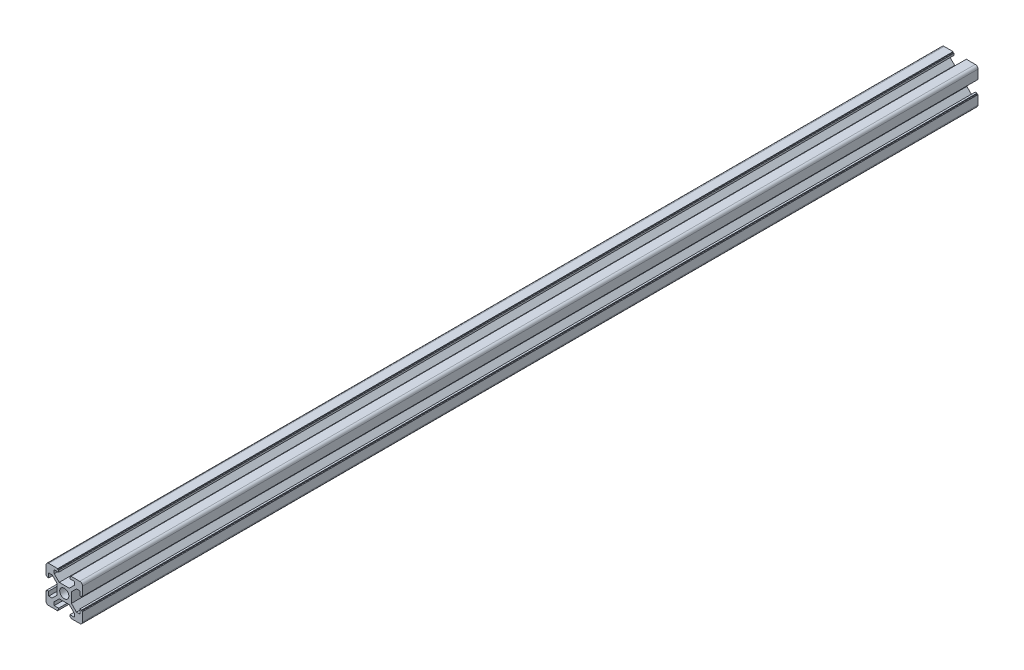
SolidWorks part; units mm, degrees
ref_plane "Plane1" through (0, 0, 0) normal (0, 0, 1) x (1, 0, 0)
ref_plane "Plane2" through (0, 0, 0) normal (0, 1, 0) x (1, 0, 0)
ref_plane "Plane3" through (0, 0, 0) normal (1, 0, 0) x (0, 0, -1)
sketch "Sketch1" plane through (0, 0, 0) normal (0, 0, 1) x (1, 0, 0)
  line L0 (-3.6, 10) -> (-3.6, 9.5)
  line L1 (-3.6, 9.5) -> (-3.1, 9.5)
  line L2 (-3.1, 9.5) -> (-3.1, 8.5)
  line L3 (-3.1, 8.5) -> (-5.5, 8.5)
  line L4 (-8.5, -10) -> (-3.6, -10)
  line L5 (-10, -8.5) -> (-10, -3.6)
  line L6 (8.5, 10) -> (3.6, 10)
  line L7 (10, 8.5) -> (10, 3.6)
  line L8 (0, 14.8756) -> (0, 0) construction
  line L9 (0, 0) -> (14.1675, 0) construction
  line L10 (-5.5, 8.5) -> (-5.5, 6.65)
  line L11 (-5.5, 6.65) -> (-2.75, 3.9)
  line L12 (-2.75, 3.9) -> (2.75, 3.9)
  line L13 (5.5, 6.65) -> (2.75, 3.9)
  line L14 (5.5, 8.5) -> (5.5, 6.65)
  line L15 (3.1, 8.5) -> (5.5, 8.5)
  line L16 (3.1, 9.5) -> (3.1, 8.5)
  line L17 (3.6, 9.5) -> (3.1, 9.5)
  line L18 (3.6, 10) -> (3.6, 9.5)
  line L19 (-3.6, 10) -> (-8.5, 10)
  line L20 (10, 3.6) -> (9.5, 3.6)
  line L21 (9.5, 3.6) -> (9.5, 3.1)
  line L22 (9.5, 3.1) -> (8.5, 3.1)
  line L23 (8.5, 3.1) -> (8.5, 5.5)
  line L24 (8.5, 5.5) -> (6.65, 5.5)
  line L25 (6.65, 5.5) -> (3.9, 2.75)
  line L26 (3.9, 2.75) -> (3.9, -2.75)
  line L27 (6.65, -5.5) -> (3.9, -2.75)
  line L28 (8.5, -5.5) -> (6.65, -5.5)
  line L29 (8.5, -3.1) -> (8.5, -5.5)
  line L30 (9.5, -3.1) -> (8.5, -3.1)
  line L31 (9.5, -3.6) -> (9.5, -3.1)
  line L32 (10, -3.6) -> (9.5, -3.6)
  line L33 (3.6, -10) -> (3.6, -9.5)
  line L34 (3.6, -9.5) -> (3.1, -9.5)
  line L35 (3.1, -9.5) -> (3.1, -8.5)
  line L36 (3.1, -8.5) -> (5.5, -8.5)
  line L37 (5.5, -8.5) -> (5.5, -6.65)
  line L38 (5.5, -6.65) -> (2.75, -3.9)
  line L39 (2.75, -3.9) -> (-2.75, -3.9)
  line L40 (-5.5, -6.65) -> (-2.75, -3.9)
  line L41 (-5.5, -8.5) -> (-5.5, -6.65)
  line L42 (-3.1, -8.5) -> (-5.5, -8.5)
  line L43 (-3.1, -9.5) -> (-3.1, -8.5)
  line L44 (-3.6, -9.5) -> (-3.1, -9.5)
  line L45 (-3.6, -10) -> (-3.6, -9.5)
  line L46 (-10, -3.6) -> (-9.5, -3.6)
  line L47 (-9.5, -3.6) -> (-9.5, -3.1)
  line L48 (-9.5, -3.1) -> (-8.5, -3.1)
  line L49 (-8.5, -3.1) -> (-8.5, -5.5)
  line L50 (-8.5, -5.5) -> (-6.65, -5.5)
  line L51 (-6.65, -5.5) -> (-3.9, -2.75)
  line L52 (-3.9, -2.75) -> (-3.9, 2.75)
  line L53 (-6.65, 5.5) -> (-3.9, 2.75)
  line L54 (-8.5, 5.5) -> (-6.65, 5.5)
  line L55 (-8.5, 3.1) -> (-8.5, 5.5)
  line L56 (-9.5, 3.1) -> (-8.5, 3.1)
  line L57 (-9.5, 3.6) -> (-9.5, 3.1)
  line L58 (-10, 3.6) -> (-9.5, 3.6)
  line L59 (3.6, -10) -> (8.5, -10)
  line L60 (-10, 3.6) -> (-10, 8.5)
  line L61 (10, -3.6) -> (10, -8.5)
  circle A0 centre (0, 0) radius 2.5
  arc A1 (-10, 8.5) -> (-8.5, 10) centre (-8.5, 8.5) cw
  arc A2 (10, 8.5) -> (8.5, 10) centre (8.5, 8.5) ccw
  arc A3 (-8.5, -10) -> (-10, -8.5) centre (-8.5, -8.5) cw
  arc A4 (8.5, -10) -> (10, -8.5) centre (8.5, -8.5) ccw
  point P0 (-10, 0)
  point P1 (10, 0)
  point P2 (0, 10)
  point P3 (0, -10)
  point P4 (0, 0)
  point P5 (-10, -10)
  point P6 (10, -10)
  point P7 (10, 10)
  point P8 (-10, 10)
  point P36 (-10, 10)
  point P39 (10, 10)
extrude "凸台-拉伸1" add sketch "Sketch1" along normal blind 490
sketch "草图1" plane through (0, 3.9, 0) normal (0, 1, 0) x (1, 0, 0)
  line L0 (2.75, -490) -> (-2.75, -490) construction
  circle A0 centre (0, -460) radius 1.7
  circle A2 centre (0, -441) radius 1.7
  dimension "D1" = 30
  dimension "D2" = 19
extrude "切除-拉伸2" cut sketch "草图1" against normal through all
